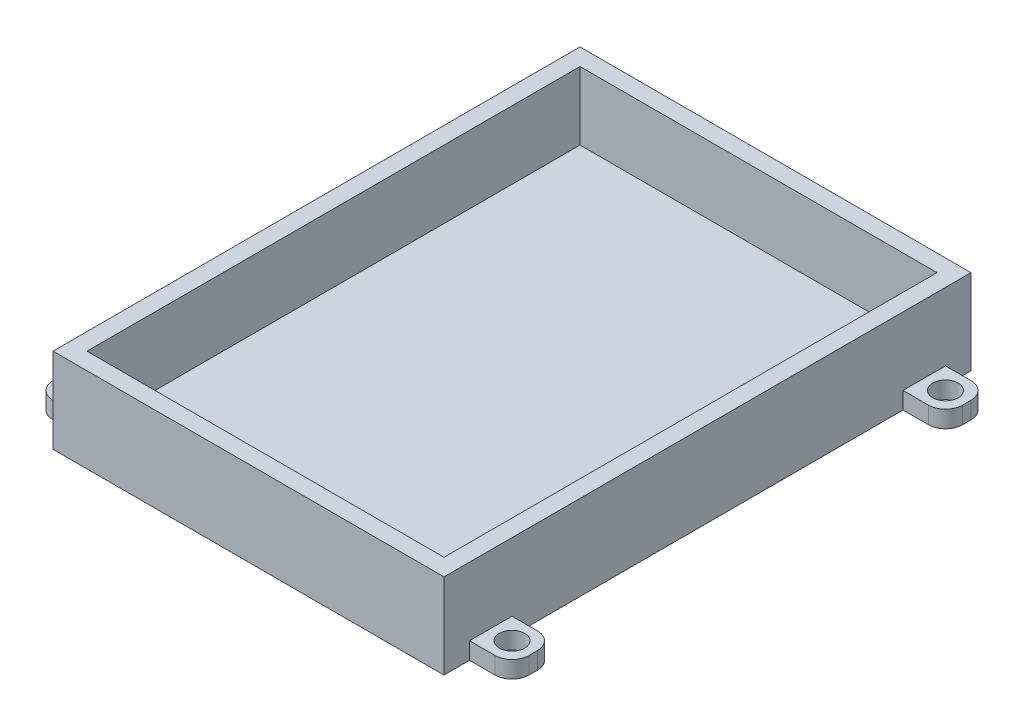
SolidWorks part; units mm, degrees
ref_plane "前视基准面" through (0, 0, 0) normal (0, 0, 1) x (1, 0, 0)
ref_plane "上视基准面" through (0, 0, 0) normal (0, 1, 0) x (1, 0, 0)
ref_plane "右视基准面" through (0, 0, 0) normal (1, 0, 0) x (0, 0, -1)
other "Configuration Table"
sketch "草图1" plane through (0, 0, 0) normal (0, 1, 0) x (1, 0, 0)
  line L1 (-30.2098, 29.8741) -> (15.7902, 29.8741)
  line L2 (-30.2098, 29.8741) -> (-30.2098, -32.1259)
  line L3 (-30.2098, -32.1259) -> (15.7902, -32.1259)
  line L4 (15.7902, 29.8741) -> (15.7902, -32.1259)
  dimension "D1" = 62
  dimension "D2" = 46
extrude "凸台-拉伸1" add sketch "草图1" along normal blind 8
sketch "草图2" plane through (0, 8, 0) normal (0, 1, 0) x (1, 0, 0)
  line L0 (-30.2098, 29.8741) -> (-30.2098, -32.1259) construction
  line L1 (-28.2098, 27.8741) -> (13.7902, 27.8741)
  line L2 (-28.2098, 27.8741) -> (-28.2098, -30.1259)
  line L3 (-28.2098, -30.1259) -> (13.7902, -30.1259)
  line L4 (13.7902, 27.8741) -> (13.7902, -30.1259)
  line L5 (-30.2098, -32.1259) -> (15.7902, -32.1259) construction
  dimension "D1" = 58
  dimension "D2" = 42
  dimension "D3" = 2
  dimension "D4" = 2
extrude "切除-拉伸1" cut sketch "草图2" against normal blind 8
sketch "草图3" plane through (0, 0, 0) normal (0, -1, 0) x (1, 0, 0)
  line L0 (-30.2098, -29.8741) -> (-30.2098, 32.1259) construction
  line L1 (-30.2098, 32.1259) -> (15.7902, 32.1259)
  line L2 (-30.2098, 32.1259) -> (-30.2098, 29.1259)
  line L3 (-30.2098, -29.8741) -> (15.7902, -29.8741)
  line L4 (15.7902, 32.1259) -> (15.7902, -29.8741)
  line L5 (-30.2098, 32.1259) -> (15.7902, 32.1259) construction
  line L6 (-30.2098, 24.1259) -> (-30.2098, -29.8741)
  line L7 (-30.2098, 29.1259) -> (-33.2098, 29.1259)
  line L9 (-30.2098, 24.1259) -> (-33.2098, 24.1259)
  line L10 (-35.2098, 27.1259) -> (-35.2098, 26.1259)
  line L11 (-7.2098, 30.1259) -> (-7.2098, -29.8741) construction
  line L13 (-30.2098, 1.1259) -> (15.7902, 1.1259) construction
  line L14 (-30.2098, -21.8741) -> (-33.2098, -21.8741)
  line L15 (-35.2098, -24.8741) -> (-35.2098, -23.8741)
  line L16 (-30.2098, -26.8741) -> (-33.2098, -26.8741)
  line L17 (15.7902, -26.8741) -> (18.7902, -26.8741)
  line L18 (20.7902, -24.8741) -> (20.7902, -23.8741)
  line L19 (15.7902, -21.8741) -> (18.7902, -21.8741)
  line L20 (20.7902, 27.1259) -> (20.7902, 26.1259)
  line L21 (15.7902, 24.1259) -> (18.7902, 24.1259)
  line L22 (15.7902, 29.1259) -> (18.7902, 29.1259)
  circle A1 centre (-32.7098, 26.6259) radius 1.5
  circle A2 centre (-32.7098, -24.3741) radius 1.5
  circle A3 centre (18.2902, -24.3741) radius 1.5
  circle A4 centre (18.2902, 26.6259) radius 1.5
  arc A5 (-35.2098, 27.1259) -> (-33.2098, 29.1259) centre (-33.2098, 27.1259) cw
  arc A6 (-33.2098, 24.1259) -> (-35.2098, 26.1259) centre (-33.2098, 26.1259) cw
  arc A7 (-35.2098, -24.8741) -> (-33.2098, -26.8741) centre (-33.2098, -24.8741) ccw
  arc A8 (-35.2098, -23.8741) -> (-33.2098, -21.8741) centre (-33.2098, -23.8741) cw
  arc A9 (18.7902, 24.1259) -> (20.7902, 26.1259) centre (18.7902, 26.1259) ccw
  arc A10 (20.7902, 27.1259) -> (18.7902, 29.1259) centre (18.7902, 27.1259) ccw
  arc A11 (20.7902, -24.8741) -> (18.7902, -26.8741) centre (18.7902, -24.8741) cw
  arc A12 (20.7902, -23.8741) -> (18.7902, -21.8741) centre (18.7902, -23.8741) ccw
  point P39 (-35.2098, 29.1259)
  point P42 (-35.2098, 24.1259)
  point P45 (-35.2098, -26.8741)
  point P48 (-35.2098, -21.8741)
  point P51 (20.7902, 24.1259)
  point P54 (20.7902, 29.1259)
  point P57 (20.7902, -26.8741)
  point P60 (20.7902, -21.8741)
  line M1 (13.7902, -27.8741) -> (-28.2098, -27.8741)
  line M2 (-28.2098, -27.8741) -> (-28.2098, 30.1259)
  line M3 (-28.2098, 30.1259) -> (13.7902, 30.1259)
  line M4 (13.7902, 30.1259) -> (13.7902, -27.8741)
  line M5 (-30.2098, 32.1259) -> (-30.2098, -29.8741)
  line M6 (-30.2098, -29.8741) -> (15.7902, -29.8741)
  line M7 (15.7902, -29.8741) -> (15.7902, 32.1259)
  line M8 (15.7902, 32.1259) -> (-30.2098, 32.1259)
  dimension "D4" = 3
  dimension "D7" = 2
  dimension "D8" = 2
  dimension "D9" = 2
  dimension "D10" = 2
  dimension "D1" = 3
  dimension "D2" = 5
  dimension "D3" = 5
  dimension "D5" = 2.5
  dimension "D6" = 2.5
extrude "凸台-拉伸2" add sketch "草图3" along normal blind 2 contours A6 L9 L7 A5 L10 A1 M5 | L6 L4 M8 M5 M6 M7 M4 M1 M2 M3 | L20 A10 L22 L4 L21 A9 A4 | A8 L15 A7 L16 L6 L14 A2 | L18 A12 L19 L4 L17 A11 A3 | M1 M4 M3 M2
